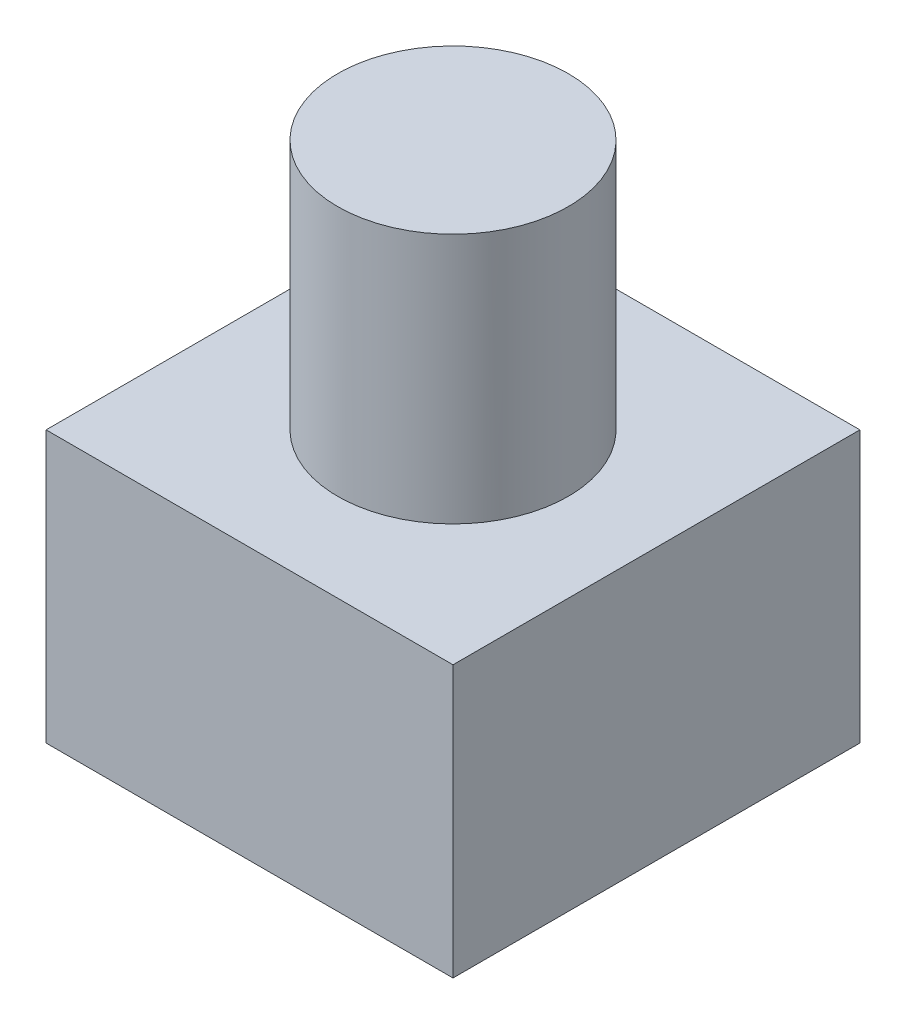
SolidWorks part; units mm, degrees
ref_plane "Front Plane" through (0, 0, 0) normal (0, 0, 1) x (1, 0, 0)
ref_plane "Top Plane" through (0, 0, 0) normal (0, 1, 0) x (1, 0, 0)
ref_plane "Right Plane" through (0, 0, 0) normal (1, 0, 0) x (0, 0, -1)
sketch "Sketch1" plane through (0, 0, 0) normal (0, 1, 0) x (1, 0, 0)
  line L0 (3, 6) -> (3, -0.4273) construction
  line L1 (0, 0) -> (6, 0)
  line L2 (0, 0) -> (0, 6)
  line L3 (0, 6) -> (6, 6)
  line L4 (6, 0) -> (6, 6)
  line L5 (0, 3) -> (6.5244, 3) construction
  dimension "D1" = 6
  dimension "D2" = 6
extrude "Boss-Extrude1" add sketch "Sketch1" along normal blind 4
sketch "Sketch2" plane through (0, 4, 0) normal (0, 1, 0) x (1, 0, 0)
  line L0 (0, 6) -> (6, 0) construction
  circle A0 centre (3, 3) radius 1.7
  point P6 (3, 3)
  dimension "D1" = 3.4
extrude "Boss-Extrude2" add sketch "Sketch2" along normal blind 3.7
ref_plane "Plane2" through (6, 4, -6) normal (-1, 0, 0) x (0, 0, 1)
